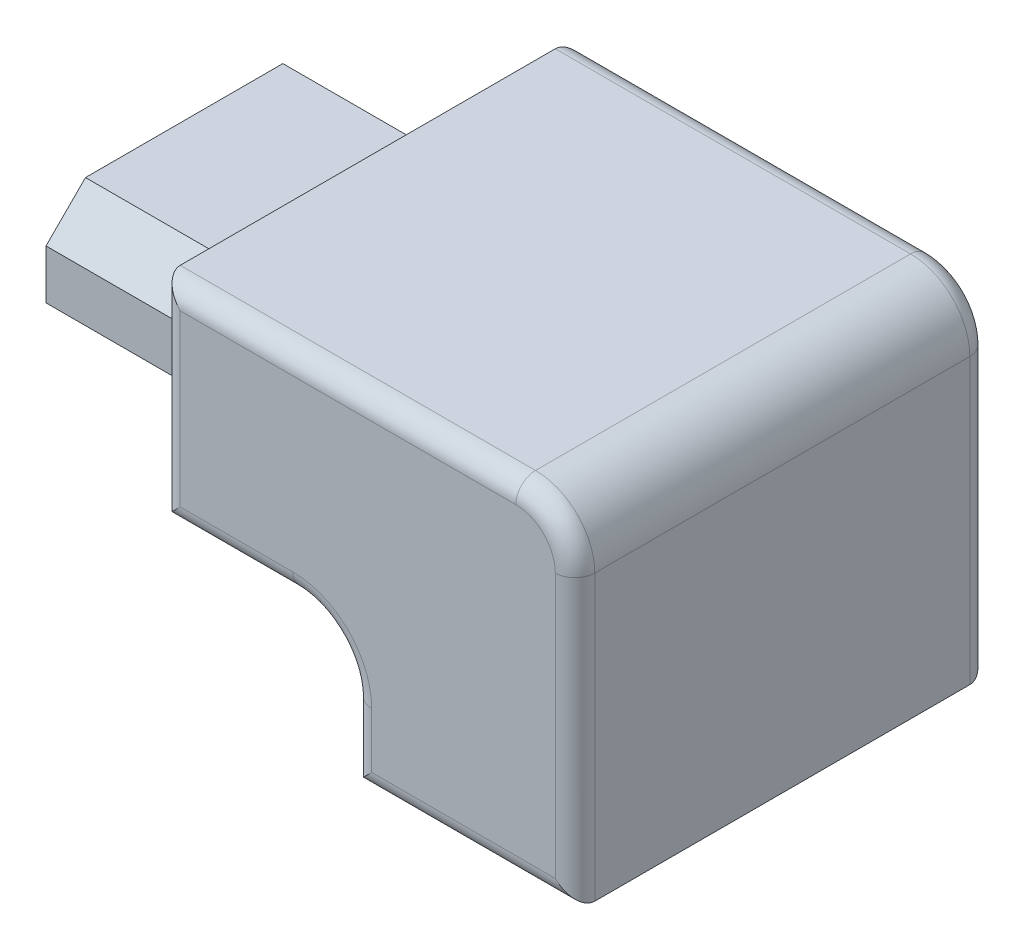
SolidWorks part; units mm, degrees
ref_plane "前视基准面" through (0, 0, 0) normal (0, 0, 1) x (1, 0, 0)
ref_plane "上视基准面" through (0, 0, 0) normal (0, 1, 0) x (1, 0, 0)
ref_plane "右视基准面" through (0, 0, 0) normal (1, 0, 0) x (0, 0, -1)
sketch "草图1" plane through (0, 0, 0) normal (0, 0, 1) x (1, 0, 0)
  line L0 (0, 17.4) -> (0, 0)
  line L1 (-11.3, 6.8) -> (-21, 6.8)
  line L3 (0, 17.4) -> (-21, 17.4)
  line L4 (-21, 6.8) -> (-21, 17.4)
  line L7 (0, 0) -> (-11.3, 0)
  line L8 (-11.3, 6.8) -> (-11.3, 0)
  point P0 (0, 0)
  dimension "D1" = 17.4
  dimension "D2" = 21
  dimension "D3" = 10.6
  dimension "D4" = 11.3
extrude "凸台-拉伸1" add sketch "草图1" along normal blind 21
sketch "草图2" plane through (-21, 0, 0) normal (-1, 0, 0) x (0, 0, 1)
  line L0 (10.5, 6.8) -> (10.5, 17.4) construction
  line L1 (21, 6.8) -> (0, 6.8) construction
  line L2 (21, 17.4) -> (0, 17.4) construction
  line L3 (5.5, 14.35) -> (3.5, 12.35)
  line L4 (17.5, 9.85) -> (3.5, 9.85)
  line L5 (17.5, 9.85) -> (17.5, 12.35)
  line L6 (15.5, 14.35) -> (5.5, 14.35)
  line L7 (3.5, 9.85) -> (3.5, 12.35)
  line L8 (17.5, 9.85) -> (3.5, 14.35) construction
  line L9 (17.5, 14.35) -> (3.5, 9.85) construction
  line L10 (17.5, 12.35) -> (15.5, 14.35)
  point P6 (10.5, 12.1)
  dimension "D1" = 14
  dimension "D2" = 4.5
extrude "凸台-拉伸2" add sketch "草图2" along normal blind 9.3
sketch "草图3" plane through (0, 0, 0) normal (0, -1, 0) x (1, 0, 0)
  line L0 (0, 10.5) -> (-11.3, 10.5) construction
  line L1 (0, 21) -> (0, 0) construction
  line L2 (-11.3, 21) -> (-11.3, 0) construction
  line L3 (-30.3, 3.5) -> (-30.3, 17.5) construction
  line L4 (-7.9, 3.5) -> (-5.4, 3.5)
  line L5 (-7.9, 3.5) -> (-7.9, 17.5)
  line L6 (-7.9, 17.5) -> (-5.4, 17.5)
  line L7 (-3.4, 5.5) -> (-3.4, 15.5)
  line L8 (-7.9, 3.5) -> (-3.4, 17.5) construction
  line L9 (-7.9, 17.5) -> (-3.4, 3.5) construction
  line L10 (-5.4, 17.5) -> (-3.4, 15.5)
  line L11 (-5.4, 3.5) -> (-3.4, 5.5)
  point P6 (-5.65, 10.5)
  point P13 (-8.3796, 17.5)
  dimension "D1" = 4.5
extrude "切除-拉伸1" cut sketch "草图3" against normal blind 0.1
fillet "圆角1" radius 3 2 edges at (-11.3, 6.8, 10.5) (0, 17.4, 10.5)
fillet "圆角2" radius 1 16 edges at (-21, 12.1, 0) (-17.65, 6.8, 0) (-12.1787, 5.9213, 0) (-11.3, 1.9, 0) (-5.65, 0, 0) (0, 7.2, 0) (-0.8787, 16.5213, 0) (-12, 17.4, 0) (-5.65, 0, 21) (-11.3, 1.9, 21) (-12.1787, 5.9213, 21) (-17.65, 6.8, 21) (-21, 12.1, 21) (-12, 17.4, 21) (-0.8787, 16.5213, 21) (0, 7.2, 21)
